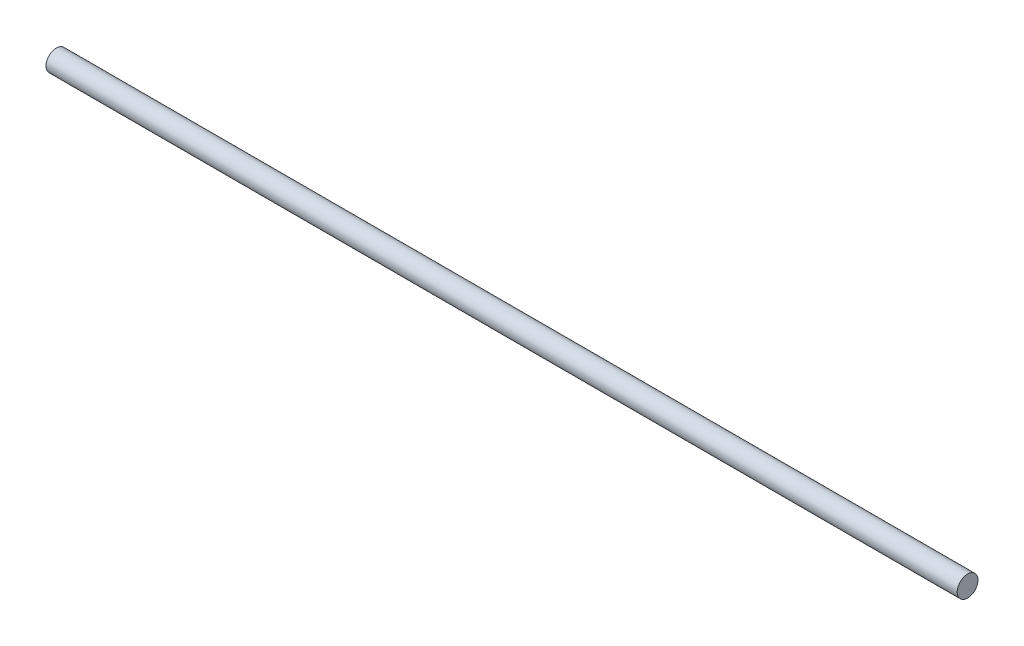
SolidWorks part; units mm, degrees
ref_plane "前视基准面" through (0, 0, 0) normal (0, 0, 1) x (1, 0, 0)
ref_plane "上视基准面" through (0, 0, 0) normal (0, 1, 0) x (1, 0, 0)
ref_plane "右视基准面" through (0, 0, 0) normal (1, 0, 0) x (0, 0, -1)
sketch "草图1" plane through (0, 0, 0) normal (1, 0, 0) x (0, 0, -1)
  circle A0 centre (0, 0) radius 4
  dimension "D1" = 8
extrude "凸台-拉伸1" add sketch "草图1" along normal blind 350
